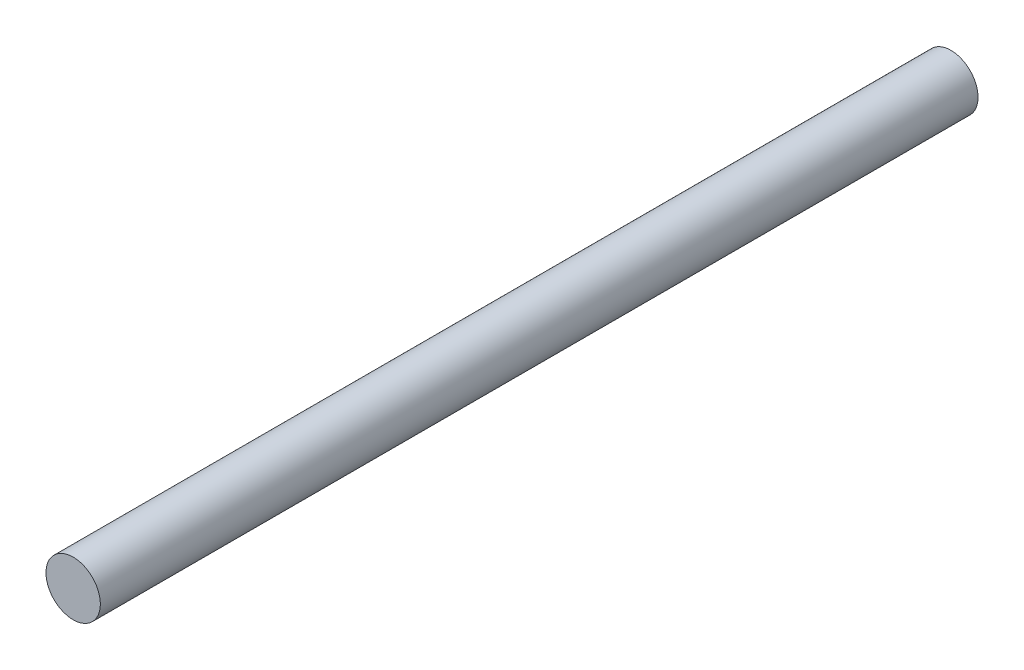
SolidWorks part; units mm, degrees
ref_plane "Front" through (0, 0, 0) normal (0, 0, 1) x (1, 0, 0)
ref_plane "Top" through (0, 0, 0) normal (0, 1, 0) x (1, 0, 0)
ref_plane "Right" through (0, 0, 0) normal (1, 0, 0) x (0, 0, -1)
sketch "Sketch1" plane through (0, 0, 0) normal (0, 0, 1) x (1, 0, 0)
  circle A0 centre (0, 0) radius 2.5
extrude "Boss-Extrude1" add sketch "Sketch1" along normal blind 304.8
sketch "For Drawing" plane through (0, 0, 0) normal (0, 0, 1) x (1, 0, 0)
  circle A0 centre (0, 0) radius 2.5
  circle A1 centre (0, 0) radius 2.5 construction
  dimension "Diameter" = 5
sketch "Break Point" plane through (0, 0, 0) normal (1, 0, 0) x (0, 0, -1)
  line L0 (-304.8, 0) -> (-297.3, 0)
  line L1 (-304.8, 2.5) -> (-304.8, -2.5) construction
  line L2 (0, 0) -> (-7.5, 0)
  line L3 (-7.5, -2.5) -> (-7.5, 2.5) construction
  line L4 (0, 2.5) -> (-304.8, 2.5) construction
  line L5 (-297.3, -2.5) -> (-297.3, 2.5) construction
  point P12 (-7.5, 0)
  point P15 (-297.3, 0)
  dimension "D1" = 7.5
sketch "Sketch2" plane through (0, 0, 304.8) normal (0, 0, 1) x (1, 0, 0)
  circle A0 centre (0, 0) radius 2.5 construction
  circle A1 centre (0, 0) radius 2.5
extrude "Cut-Extrude1" cut sketch "Sketch2" against normal blind 224
equation "\"D1@Break Point\"=\"Diameter@Sketch1\" * 1.5"
